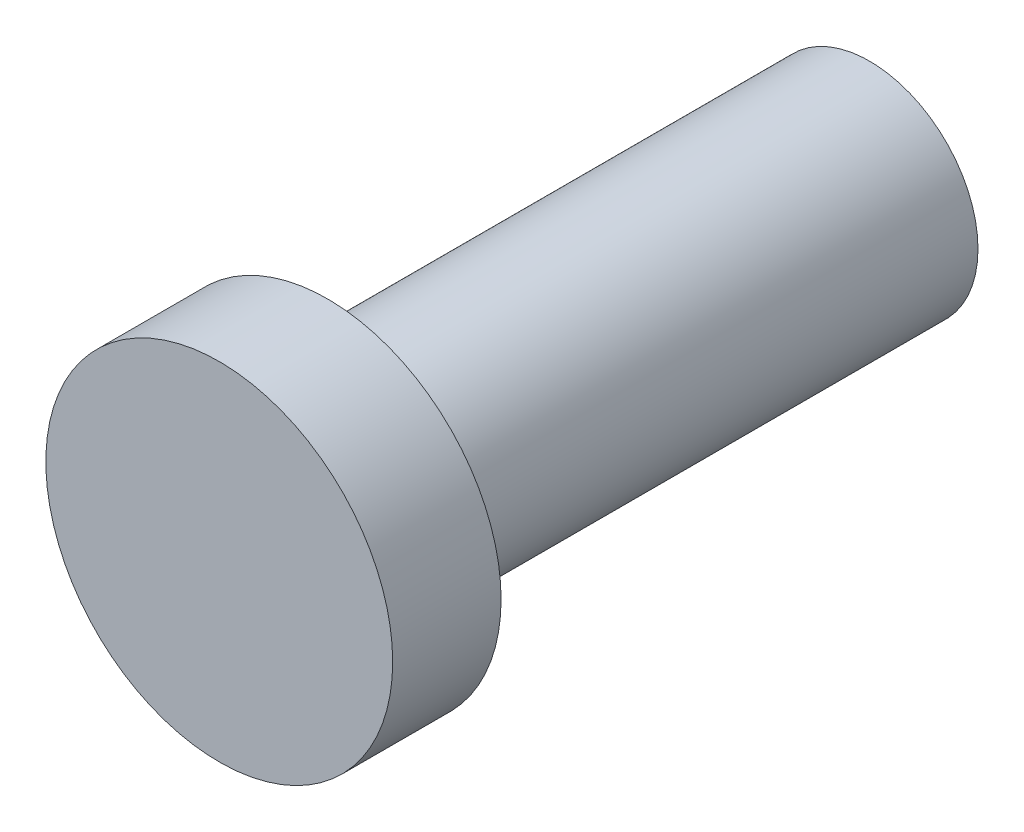
SolidWorks part; units mm, degrees
ref_plane "Front Plane" through (0, 0, 0) normal (0, 0, 1) x (1, 0, 0)
ref_plane "Top Plane" through (0, 0, 0) normal (0, 1, 0) x (1, 0, 0)
ref_plane "Right Plane" through (0, 0, 0) normal (1, 0, 0) x (0, 0, -1)
sketch "Sketch1" plane through (0, 0, 0) normal (0, 0, 1) x (1, 0, 0)
  circle A0 centre (0, 0) radius 5
  dimension "D1" = 10
extrude "Boss-Extrude1" add sketch "Sketch1" along normal blind 25
sketch "Sketch2" plane through (0, 0, 25) normal (0, 0, 1) x (1, 0, 0)
  circle A0 centre (0, 0) radius 8
extrude "Boss-Extrude2" add sketch "Sketch2" along normal blind 5
